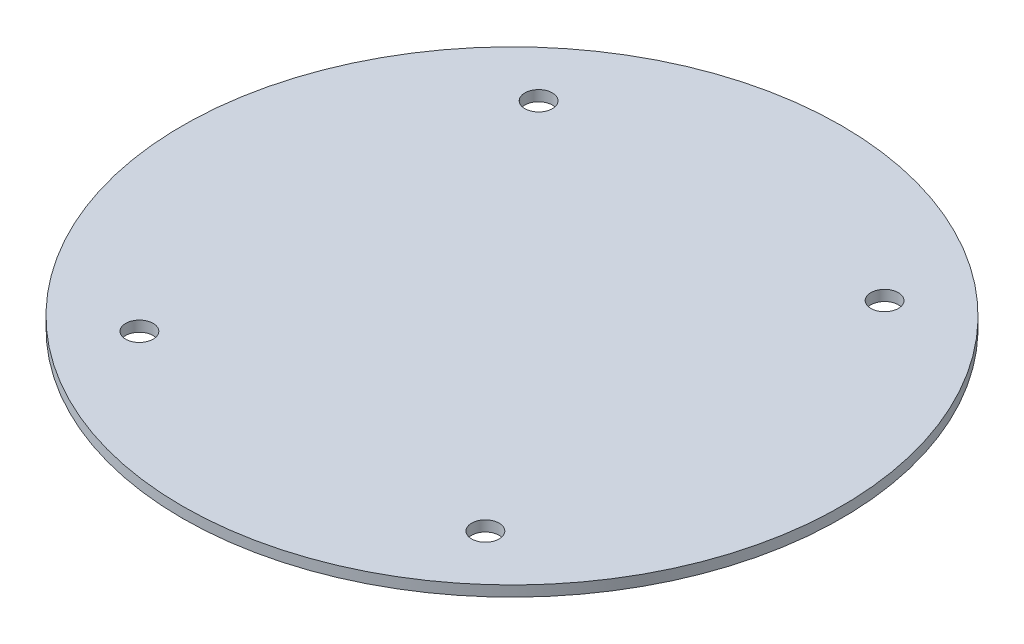
SolidWorks part; units mm, degrees
ref_plane "Front Plane" through (0, 0, 0) normal (0, 0, 1) x (1, 0, 0)
ref_plane "Top Plane" through (0, 0, 0) normal (0, 1, 0) x (1, 0, 0)
ref_plane "Right Plane" through (0, 0, 0) normal (1, 0, 0) x (0, 0, -1)
sketch "Sketch1" plane through (0, 0, 0) normal (0, 1, 0) x (1, 0, 0)
  circle A0 centre (0, 0) radius 49.53
  dimension "D1" = 99.06
extrude "Extrude1" add sketch "Sketch1" along normal blind 1.5875
sketch "Sketch2" plane through (0, 1.5875, 0) normal (0, 1, 0) x (-1, 0, 0)
  circle A0 centre (-26, -30) radius 2.0638
  dimension "D3" = 4.1275
  dimension "D1" = 30
  dimension "D2" = 26
extrude "Extrude2" cut sketch "Sketch2" against normal blind 10
mirror "Mirror1" about plane through (0, 0, 0) normal (1, 0, 0) of "Extrude2"
mirror "Mirror3" about plane through (0, 0, 0) normal (0, 0, 1) of "Mirror1", "Extrude2"
